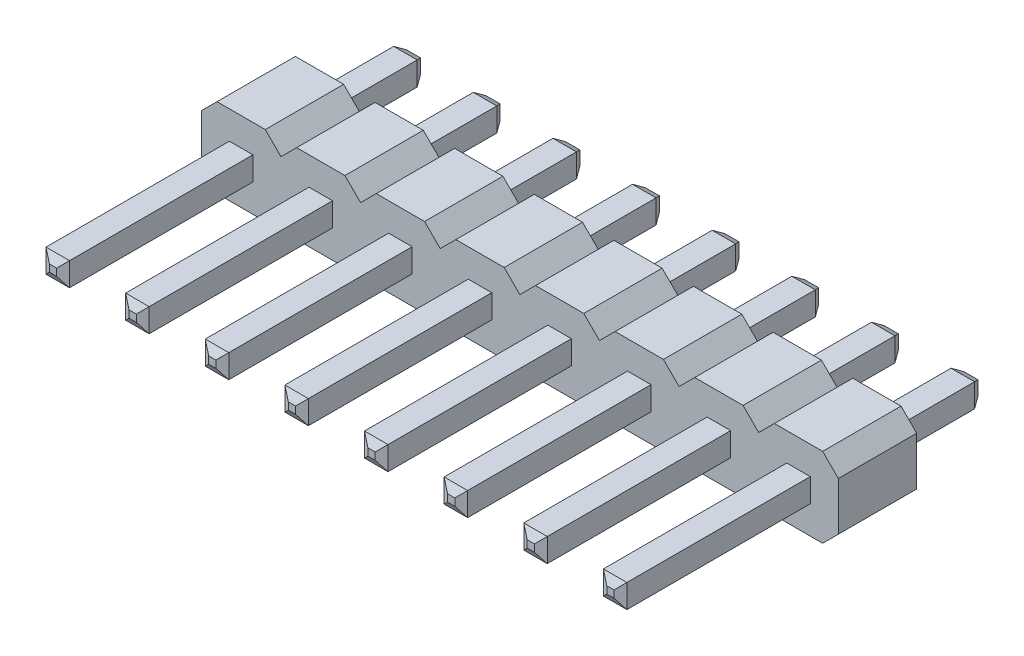
SolidWorks part; units mm, degrees
material "ABSOranžová"
ref_plane "Horní rovina" through (0, 0, 0) normal (0, 0, 1) x (1, 0, 0)
ref_plane "Přední rovina" through (0, 0, 0) normal (0, 1, 0) x (1, 0, 0)
ref_plane "Pravá rovina" through (0, 0, 0) normal (1, 0, 0) x (0, 0, -1)
sketch "Skica1" plane through (0, 0, 0) normal (0, 0, 1) x (1, 0, 0)
  line L0 (0.77, 1.27) -> (1.27, 0.77)
  line L1 (-0.77, 1.27) -> (0.77, 1.27)
  line L2 (-1.27, 0.77) -> (-1.27, -0.77)
  line L3 (-0.77, -1.27) -> (0.77, -1.27)
  line L4 (1.27, 0.77) -> (1.27, -0.77)
  line L5 (-1.27, 1.27) -> (1.27, -1.27) construction
  line L6 (-1.27, -1.27) -> (1.27, 1.27) construction
  line L7 (-0.77, 1.27) -> (-1.27, 0.77)
  line L8 (-1.27, -0.77) -> (-0.77, -1.27)
  line L9 (1.27, -0.77) -> (0.77, -1.27)
  line L10 (-2.9078, 0) -> (3.8264, 0) construction
  line L11 (-0.375, 0.375) -> (0.375, 0.375)
  line L12 (-0.375, 0.375) -> (-0.375, -0.375)
  line L13 (-0.375, -0.375) -> (0.375, -0.375)
  line L14 (0.375, 0.375) -> (0.375, -0.375)
  line L15 (-0.375, 0.375) -> (0.375, -0.375) construction
  line L16 (-0.375, -0.375) -> (0.375, 0.375) construction
  point P0 (0, 0)
  point P14 (0, 0)
  dimension "D1" = 2.54
  dimension "D2" = 2.54
  dimension "D3" = 0.75
extrude "Přidat vysunutím1" add sketch "Skica1" along normal blind 2.5
pattern_linear "LinPole3" count 8 spacing 2.54 along (-1, 0, 0) of "Přidat vysunutím1"
sketch "Skica2" plane through (0, 0, 2.5) normal (0, 0, 1) x (1, 0, 0)
  line L0 (-18.155, -0.375) -> (-17.405, -0.375) construction
  line L1 (-18.155, 0.375) -> (-18.155, -0.375) construction
  line L2 (-17.405, 0.375) -> (-18.155, 0.375) construction
  line L3 (-17.405, -0.375) -> (-17.405, 0.375) construction
  line L4 (-14.865, -0.375) -> (-14.865, 0.375) construction
  line L5 (-15.615, -0.375) -> (-14.865, -0.375) construction
  line L6 (-15.615, 0.375) -> (-15.615, -0.375) construction
  line L7 (-14.865, 0.375) -> (-15.615, 0.375) construction
  line L8 (-18.155, -0.375) -> (-17.405, -0.375)
  line L9 (-18.155, 0.375) -> (-18.155, -0.375)
  line L10 (-17.405, 0.375) -> (-18.155, 0.375)
  line L11 (-17.405, -0.375) -> (-17.405, 0.375)
  line L12 (-14.865, -0.375) -> (-14.865, 0.375)
  line L13 (-15.615, -0.375) -> (-14.865, -0.375)
  line L14 (-15.615, 0.375) -> (-15.615, -0.375)
  line L15 (-14.865, 0.375) -> (-15.615, 0.375)
  line L28 (-12.325, -0.375) -> (-12.325, 0.375)
  line L29 (-13.075, -0.375) -> (-12.325, -0.375)
  line L30 (-13.075, 0.375) -> (-13.075, -0.375)
  line L31 (-12.325, 0.375) -> (-13.075, 0.375)
  line L32 (-12.325, -0.375) -> (-12.325, 0.375)
  line L33 (-13.075, -0.375) -> (-12.325, -0.375)
  line L34 (-13.075, 0.375) -> (-13.075, -0.375)
  line L35 (-12.325, 0.375) -> (-13.075, 0.375)
  line L36 (-9.785, -0.375) -> (-9.785, 0.375)
  line L37 (-10.535, -0.375) -> (-9.785, -0.375)
  line L38 (-10.535, 0.375) -> (-10.535, -0.375)
  line L39 (-9.785, 0.375) -> (-10.535, 0.375)
  line L40 (-9.785, -0.375) -> (-9.785, 0.375)
  line L41 (-10.535, -0.375) -> (-9.785, -0.375)
  line L42 (-10.535, 0.375) -> (-10.535, -0.375)
  line L43 (-9.785, 0.375) -> (-10.535, 0.375)
  line L44 (-7.245, -0.375) -> (-7.245, 0.375)
  line L45 (-7.995, -0.375) -> (-7.245, -0.375)
  line L46 (-7.995, 0.375) -> (-7.995, -0.375)
  line L47 (-7.245, 0.375) -> (-7.995, 0.375)
  line L48 (-7.245, -0.375) -> (-7.245, 0.375)
  line L49 (-7.995, -0.375) -> (-7.245, -0.375)
  line L50 (-7.995, 0.375) -> (-7.995, -0.375)
  line L51 (-7.245, 0.375) -> (-7.995, 0.375)
  line L52 (-4.705, -0.375) -> (-4.705, 0.375)
  line L53 (-5.455, -0.375) -> (-4.705, -0.375)
  line L54 (-5.455, 0.375) -> (-5.455, -0.375)
  line L55 (-4.705, 0.375) -> (-5.455, 0.375)
  line L56 (-4.705, -0.375) -> (-4.705, 0.375)
  line L57 (-5.455, -0.375) -> (-4.705, -0.375)
  line L58 (-5.455, 0.375) -> (-5.455, -0.375)
  line L59 (-4.705, 0.375) -> (-5.455, 0.375)
  line L60 (-2.165, -0.375) -> (-2.165, 0.375)
  line L61 (-2.915, -0.375) -> (-2.165, -0.375)
  line L62 (-2.915, 0.375) -> (-2.915, -0.375)
  line L63 (-2.165, 0.375) -> (-2.915, 0.375)
  line L64 (-2.165, -0.375) -> (-2.165, 0.375)
  line L65 (-2.915, -0.375) -> (-2.165, -0.375)
  line L66 (-2.915, 0.375) -> (-2.915, -0.375)
  line L67 (-2.165, 0.375) -> (-2.915, 0.375)
  line L68 (0.375, -0.375) -> (0.375, 0.375)
  line L69 (-0.375, -0.375) -> (0.375, -0.375)
  line L70 (-0.375, 0.375) -> (-0.375, -0.375)
  line L71 (0.375, 0.375) -> (-0.375, 0.375)
  line L72 (0.375, -0.375) -> (0.375, 0.375)
  line L73 (-0.375, -0.375) -> (0.375, -0.375)
  line L74 (-0.375, 0.375) -> (-0.375, -0.375)
  line L75 (0.375, 0.375) -> (-0.375, 0.375)
  dimension "D1" = 0
  dimension "D2" = 0
  dimension "D3" = 0
  dimension "D4" = 0
  dimension "D5" = 0
  dimension "D6" = 0
extrude "Přidat vysunutím2" add sketch "Skica2" along normal blind 6 and the other way blind 5.5
chamfer "Zkosení2" distance 0.15 angle 60 64 edges at (-0.375, 0, -3) (0, -0.375, -3) (0.375, 0, -3) (0, 0.375, -3) (-2.915, 0, -3) (-2.54, -0.375, -3) (-2.165, 0, -3) (-2.54, 0.375, -3) (-5.455, 0, -3) (-5.08, -0.375, -3) (-4.705, 0, -3) (-5.08, 0.375, -3) (-7.995, 0, -3) (-7.62, -0.375, -3) (-7.245, 0, -3) (-7.62, 0.375, -3) (-10.535, 0, -3) (-10.16, -0.375, -3) (-9.785, 0, -3) (-10.16, 0.375, -3) (-13.075, 0, -3) (-12.7, -0.375, -3) (-12.325, 0, -3) (-12.7, 0.375, -3) (-12.325, 0, 8.5) (-12.7, -0.375, 8.5) (-13.075, 0, 8.5) (-12.7, 0.375, 8.5) (-9.785, 0, 8.5) (-10.16, -0.375, 8.5) (-10.535, 0, 8.5) (-10.16, 0.375, 8.5) (-7.245, 0, 8.5) (-7.62, -0.375, 8.5) (-7.995, 0, 8.5) (-7.62, 0.375, 8.5) (-4.705, 0, 8.5) (-5.08, -0.375, 8.5) (-5.455, 0, 8.5) (-5.08, 0.375, 8.5) (-2.165, 0, 8.5) (-2.54, -0.375, 8.5) (-2.915, 0, 8.5) (-2.54, 0.375, 8.5) (0.375, 0, 8.5) (0, -0.375, 8.5) (-0.375, 0, 8.5) (0, 0.375, 8.5) (-17.78, -0.375, -3) (-17.405, 0, -3) (-17.78, 0.375, -3) (-18.155, 0, -3) (-14.865, 0, -3) (-15.24, 0.375, -3) (-15.615, 0, -3) (-15.24, -0.375, -3) (-17.78, 0.375, 8.5) (-17.405, 0, 8.5) (-17.78, -0.375, 8.5) (-18.155, 0, 8.5) (-15.615, 0, 8.5) (-15.24, 0.375, 8.5) (-14.865, 0, 8.5) (-15.24, -0.375, 8.5)
